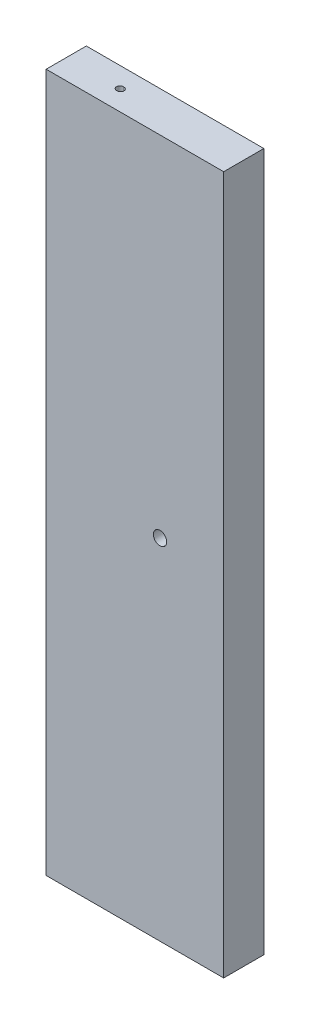
SolidWorks part; units mm, degrees
material "Beech"
ref_plane "Front Plane" through (0, 0, 0) normal (0, 0, 1) x (1, 0, 0)
ref_plane "Top Plane" through (0, 0, 0) normal (0, 1, 0) x (1, 0, 0)
ref_plane "Right Plane" through (0, 0, 0) normal (1, 0, 0) x (0, 0, -1)
sketch "Sketch1" plane through (0, 0, 0) normal (0, 0, 1) x (1, 0, 0)
  line L0 (209.353, -245.4375) -> (209.353, -248.6125) construction
  line L1 (209.353, 93.45) -> (293.4908, 93.45)
  line L2 (209.353, 93.45) -> (209.353, -237.5)
  line L3 (209.353, -237.5) -> (293.4908, -237.5)
  line L4 (350.6408, 93.45) -> (350.6408, -237.5) construction
  line L5 (293.4908, 93.45) -> (293.4908, -237.5)
  line L6 (209.353, -125) -> (209.353, -144.05) construction
  line L7 (350.6408, 0) -> (350.6408, -19.05) construction
  line L8 (293.4908, -237.5) -> (350.6408, -237.5) construction
  line L9 (293.4908, 93.45) -> (350.6408, 93.45) construction
  point P8 (0, 0)
  point P9 (289.7389, -237.5)
  point P10 (293.4908, -237.5)
  dimension "D1" = 84.1379
extrude "Boss-Extrude1" add sketch "Sketch1" along normal blind 19.05
hole_wizard "Hole1" positions "Sketch2" profile "Sketch3" legacy
sketch "Sketch2" plane through (196.653, -72.025, 386.2628) normal (-1, 0, 0) x (0, 1, 0)
  point P49 (175, 685.961)
  point P51 (175, 549.8373)
  point P53 (175, 413.7135)
  point P67 (81.55, 779.6497)
  point P73 (81.55, 652.3446)
  point P79 (62.5, 662.9534)
  point P83 (62.5, 769.041)
  point P103 (-62.5, 769.041)
  point P105 (-62.5, 662.9534)
  point P106 (-81.55, 652.3446)
  point P109 (-81.55, 779.6497)
  point P110 (-175, 413.7135)
  point P111 (-175, 549.8373)
  point P112 (-175, 685.961)
  point P115 (-82.7375, 600.3846)
  point P117 (0, 600.3846)
  point P119 (82.7375, 600.3846)
  point P129 (0, 376.7378)
  point P131 (-82.7375, 376.7378)
  point P133 (82.7375, 376.7378)
sketch "Sketch3" plane through (196.653, 102.975, -299.6982) normal (0, 1, 0) x (0, 0, 1)
  line L0 (0, 0) -> (0, 32.7039)
  line L1 (0, 32.7039) -> (1.5875, 31.75)
  line L2 (1.5875, 31.75) -> (1.5875, 4.0177)
  line L3 (1.5875, 4.0177) -> (5.08, 0)
  line L4 (5.08, 0) -> (0, 0)
  line L5 (0, -14.3089) -> (0, 102.4216) construction
  line L6 (0, 32.7039) -> (-1.5875, 31.75) construction
  line L7 (-1.5875, 4.0177) -> (-5.08, 0) construction
  dimension "Diameter" = 3.175
  dimension "Depth" = 31.75
  dimension "C-Sink Diameter" = 10.16
  dimension "C-Sink Angle" = 82
  dimension "Drill Angle" = 118
hole_wizard "Hole3" positions "Sketch6" profile "Sketch7" legacy
sketch "Sketch6" plane through (-181.0394, 112.5, 386.2628) normal (0, 1, 0) x (0.9272, 0, -0.3746)
  line L0 (48.5061, 138.7859) -> (35.9701, 0) construction
  line L5 (414.5728, 105.7206) -> (405.0235, 0) construction
  line L7 (490.0108, 170.6797) -> (621.0107, 117.7523) construction
  line L12 (503.094, 203.0616) -> (634.0938, 150.1342) construction
  line L16 (586.8736, 410.4234) -> (717.8734, 357.496) construction
  line L19 (597.4602, 127.2674) -> (610.5433, 159.6493) construction
  line L20 (610.5433, 159.6493) -> (694.3229, 367.011) construction
  line L22 (513.5613, 161.1647) -> (526.6445, 193.5466) construction
  line L23 (526.6445, 193.5466) -> (610.424, 400.9084) construction
  point P0 (46.2211, 113.4889)
  point P2 (39.3976, 37.9455)
  point P4 (412.2879, 80.4236)
  point P51 (407.3085, 25.297)
  point P56 (513.5613, 161.1647)
  point P58 (597.4602, 127.2674)
  point P61 (610.5433, 159.6493)
  point P63 (694.3229, 367.011)
  point P66 (526.6445, 193.5466)
  point P68 (610.424, 400.9084)
sketch "Sketch7" plane through (-180.6976, 112.5, 263.723) normal (1, 0, 0) x (0, 0, 1)
  line L0 (0, 0) -> (0, 39.0539)
  line L1 (0, 39.0539) -> (1.5875, 38.1)
  line L2 (1.5875, 38.1) -> (1.5875, 4.0177)
  line L3 (1.5875, 4.0177) -> (5.08, 0)
  line L4 (5.08, 0) -> (0, 0)
  line L5 (0, -14.3089) -> (0, 102.4216) construction
  line L6 (0, 39.0539) -> (-1.5875, 38.1) construction
  line L7 (-1.5875, 4.0177) -> (-5.08, 0) construction
  dimension "Diameter" = 3.175
  dimension "Depth" = 38.1
  dimension "C-Sink Diameter" = 10.16
  dimension "C-Sink Angle" = 82
  dimension "Drill Angle" = 118
hole_wizard "1/4 (0.25) Diameter Hole1" positions "Sketch10" profile "Sketch11" hole size "1/4" standard "ANSI Inch" end condition through all
sketch "Sketch10" plane through (0, 0, 0) normal (0, 0, -1) x (-1, 0, 0)
  line L0 (-209.353, -72.025) -> (-293.4908, -72.025) construction
  line L1 (-209.353, 93.45) -> (-209.353, -237.5) construction
  line L4 (-293.4908, -237.5) -> (-293.4908, 93.45) construction
  circle A0 centre (-263.3283, -72.025) radius 30.1625
  point P0 (-263.3283, -72.025)
  dimension "D1" = 60.325
sketch "Sketch11" plane through (263.3283, -72.025, 0) normal (1, 0, 0) x (0, 1, 0)
  line L0 (0, 0) -> (0, 19.05)
  line L1 (0, 19.05) -> (3.175, 19.05)
  line L2 (3.175, 19.05) -> (3.175, 0)
  line L5 (3.175, 0) -> (0, 0)
  line L11 (0, -6.35) -> (0, 107.95) construction
  dimension "Thru Hole Dia." = 6.35
  dimension "Thru Hole Depth" = 19.05
hole_wizard "Hole4" positions "Sketch12" profile "Sketch13" legacy
sketch "Sketch12" plane through (196.653, -72.025, 609.9096) normal (-1, 0, 0) x (0, 1, 0)
  point P49 (175, 685.961)
  point P51 (175, 549.8373)
  point P53 (175, 413.7135)
  point P67 (81.55, 779.6497)
  point P73 (81.55, 652.3446)
  point P79 (62.5, 662.9534)
  point P83 (62.5, 769.041)
  point P103 (-62.5, 769.041)
  point P105 (-62.5, 662.9534)
  point P106 (-81.55, 652.3446)
  point P109 (-81.55, 779.6497)
  point P110 (-175, 413.7135)
  point P111 (-175, 549.8373)
  point P112 (-175, 685.961)
  point P115 (-82.7375, 600.3846)
  point P117 (0, 600.3846)
  point P119 (82.7375, 600.3846)
  point P129 (0, 376.7378)
  point P131 (-82.7375, 376.7378)
  point P133 (82.7375, 376.7378)
sketch "Sketch13" plane through (196.653, 102.975, -76.0514) normal (0, 1, 0) x (0, 0, 1)
  line L0 (0, 0) -> (0, 32.7039)
  line L1 (0, 32.7039) -> (1.5875, 31.75)
  line L2 (1.5875, 31.75) -> (1.5875, 4.0177)
  line L3 (1.5875, 4.0177) -> (5.08, 0)
  line L4 (5.08, 0) -> (0, 0)
  line L5 (0, -14.3089) -> (0, 102.4216) construction
  line L6 (0, 32.7039) -> (-1.5875, 31.75) construction
  line L7 (-1.5875, 4.0177) -> (-5.08, 0) construction
  dimension "Diameter" = 3.175
  dimension "Depth" = 31.75
  dimension "C-Sink Diameter" = 10.16
  dimension "C-Sink Angle" = 82
  dimension "Drill Angle" = 118
hole_wizard "Hole5" positions "Sketch14" profile "Sketch15" legacy
sketch "Sketch14" plane through (-181.0394, 112.5, 609.9096) normal (0, 1, 0) x (0.9272, 0, -0.3746)
  line L0 (48.5061, 138.7859) -> (35.9701, 0) construction
  line L5 (414.5728, 105.7206) -> (405.0235, 0) construction
  line L7 (490.0108, 170.6797) -> (621.0107, 117.7523) construction
  line L12 (503.094, 203.0616) -> (633.5357, 148.7528) construction
  line L16 (586.8736, 410.4234) -> (717.8734, 357.496) construction
  line L19 (597.4602, 127.2674) -> (610.4136, 158.3796) construction
  line L20 (610.4136, 158.3796) -> (694.6524, 366.8779) construction
  line L22 (513.5613, 161.1647) -> (526.8815, 193.1578) construction
  line L23 (526.8815, 193.1578) -> (610.7629, 400.7715) construction
  point P0 (46.2211, 113.4889)
  point P2 (39.3976, 37.9455)
  point P4 (412.2879, 80.4236)
  point P51 (407.3085, 25.297)
  point P56 (513.5613, 161.1647)
  point P58 (597.4602, 127.2674)
  point P61 (610.4136, 158.3796)
  point P63 (694.6524, 366.8779)
  point P66 (526.8815, 193.1578)
  point P68 (610.7629, 400.7715)
sketch "Sketch15" plane through (-180.6976, 112.5, 487.3699) normal (1, 0, 0) x (0, 0, 1)
  line L0 (0, 0) -> (0, 39.0539)
  line L1 (0, 39.0539) -> (1.5875, 38.1)
  line L2 (1.5875, 38.1) -> (1.5875, 4.0177)
  line L3 (1.5875, 4.0177) -> (5.08, 0)
  line L4 (5.08, 0) -> (0, 0)
  line L5 (0, -14.3089) -> (0, 102.4216) construction
  line L6 (0, 39.0539) -> (-1.5875, 38.1) construction
  line L7 (-1.5875, 4.0177) -> (-5.08, 0) construction
  dimension "Diameter" = 3.175
  dimension "Depth" = 38.1
  dimension "C-Sink Diameter" = 10.16
  dimension "C-Sink Angle" = 82
  dimension "Drill Angle" = 118
